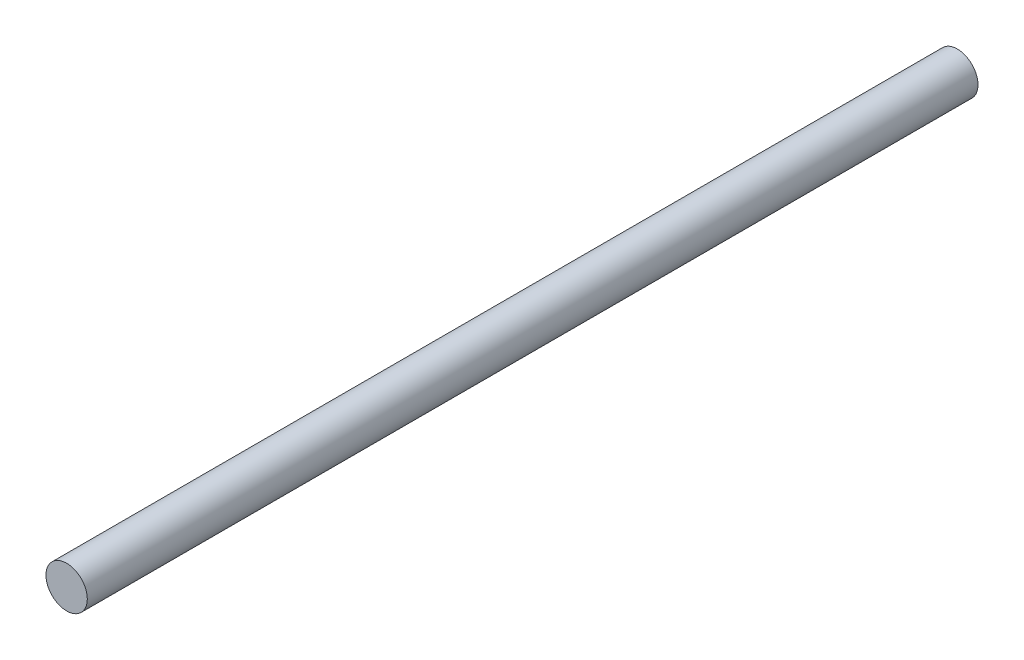
SolidWorks part; units mm, degrees
ref_plane "Front Plane" through (0, 0, 0) normal (1, 0, 0) x (0, 1, 0)
ref_plane "Top Plane" through (0, 0, 0) normal (0, 0, 1) x (0, 1, 0)
ref_plane "Right Plane" through (0, 0, 0) normal (0, 1, 0) x (-1, 0, 0)
sketch "Sketch1" plane through (0, 0, 0) normal (0, 0, 1) x (0, 1, 0)
  circle A0 centre (0, 0) radius 3.25
  dimension "D1" = 6.5
extrude "Boss-Extrude1" add sketch "Sketch1" along normal blind 140
